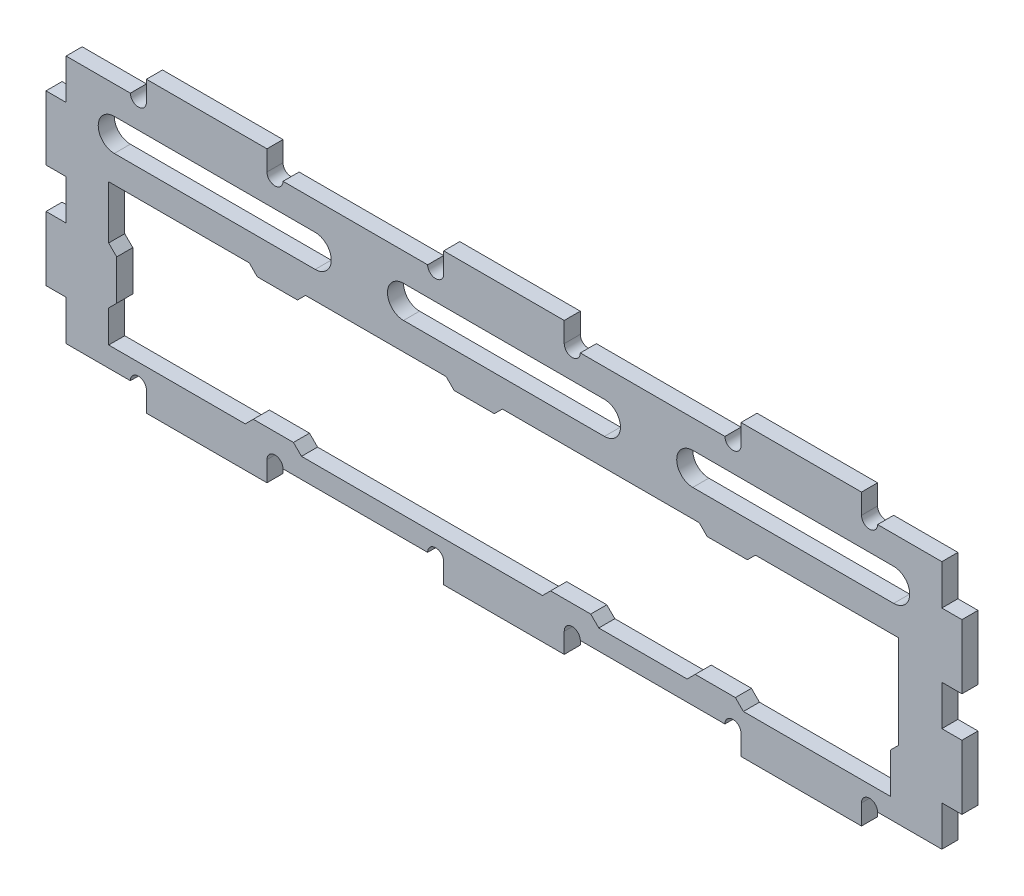
SolidWorks part; units mm, degrees
ref_plane "前视基准面" through (0, 0, 0) normal (0, 0, 1) x (1, 0, 0)
ref_plane "上视基准面" through (0, 0, 0) normal (0, 1, 0) x (1, 0, 0)
ref_plane "右视基准面" through (0, 0, 0) normal (1, 0, 0) x (0, 0, -1)
sketch "草图1" plane through (0, 0, 0) normal (0, 0, 1) x (1, 0, 0)
  line L0 (0, 13) -> (109, 13) construction
  line L1 (0, 0) -> (109, 0)
  line L2 (0, 0) -> (0, 31)
  line L3 (0, 31) -> (109, 31)
  line L4 (109, 0) -> (109, 31)
  line L5 (23.3, 3.5) -> (28.3, 3.5)
  line L6 (23.8, 19.1) -> (28.8, 19.1)
  line L7 (6.3, 12.5) -> (6.3, 7.5)
  line L8 (102.6, 7.5) -> (102.6, 2.5)
  line L9 (65.3, 3.5) -> (60.3, 3.5)
  line L10 (78.3, 3.5) -> (83.3, 3.5)
  line L11 (23.3, 3.5) -> (22.3, 2.5)
  line L12 (22.3, 2.5) -> (5.3, 2.5)
  line L13 (5.3, 2.5) -> (5.3, 6.5)
  line L14 (5.3, 6.5) -> (6.3, 7.5)
  line L15 (28.3, 3.5) -> (29.3, 2.5)
  line L16 (60.3, 3.5) -> (59.3, 2.5)
  line L17 (65.3, 3.5) -> (66.3, 2.5)
  line L18 (78.3, 3.5) -> (77.3, 2.5)
  line L19 (83.3, 3.5) -> (84.3, 2.5)
  line L20 (29.3, 2.5) -> (59.3, 2.5)
  line L21 (66.3, 2.5) -> (77.3, 2.5)
  line L22 (84.3, 2.5) -> (102.6, 2.5)
  line L23 (102.6, 7.5) -> (103.6, 8.5)
  line L24 (103.6, 8.5) -> (103.6, 20.1)
  line L25 (23.8, 19.1) -> (22.8, 20.1)
  line L26 (22.8, 20.1) -> (5.3, 20.1)
  line L27 (6.3, 12.5) -> (5.3, 13.5)
  line L28 (5.3, 13.5) -> (5.3, 20.1)
  line L29 (48.3, 19.1) -> (53.3, 19.1)
  line L30 (79.8, 19.1) -> (84.8, 19.1)
  line L31 (84.8, 19.1) -> (85.8, 20.1)
  line L32 (79.8, 19.1) -> (78.8, 20.1)
  line L33 (53.3, 19.1) -> (54.3, 20.1)
  line L34 (48.3, 19.1) -> (47.3, 20.1)
  line L35 (28.8, 19.1) -> (29.8, 20.1)
  line L36 (29.8, 20.1) -> (47.3, 20.1)
  line L37 (54.3, 20.1) -> (78.8, 20.1)
  line L38 (85.8, 20.1) -> (103.6, 20.1)
  point P15 (6.3, 10)
  dimension "D1" = 31
  dimension "D2" = 109
  dimension "D3" = 13
  dimension "D4" = 9.5
  dimension "D5" = 15.6
  dimension "D6" = 96.3
  dimension "D7" = 6.4
  dimension "D8" = 17
  dimension "D9" = 5
  dimension "D10" = 59
  dimension "D11" = 5
  dimension "D12" = 77
  dimension "D13" = 5
  dimension "D14" = 10
  dimension "D15" = 5
  dimension "D16" = 135
  dimension "D17" = 1
  dimension "D18" = 1
  dimension "D19" = 5
  dimension "D20" = 22.5
  dimension "D21" = 5
  dimension "D22" = 1
  dimension "D23" = 47
  dimension "D24" = 5
  dimension "D25" = 78.5
  dimension "D26" = 5
  dimension "D28" = 1
extrude "凸台-拉伸1" add sketch "草图1" along normal blind 2
sketch "草图2" plane through (0, 0, 2) normal (0, 0, 1) x (1, 0, 0)
  line L0 (0, 31) -> (0, 0) construction
  line L1 (0, 26) -> (-2.5, 26)
  line L2 (0, 26) -> (0, 18)
  line L3 (0, 18) -> (-2.5, 18)
  line L4 (-2.5, 26) -> (-2.5, 18)
  line L5 (109, 31) -> (0, 31) construction
  line L6 (0, 5) -> (-2.5, 5)
  line L7 (0, 5) -> (0, 13)
  line L8 (0, 13) -> (-2.5, 13)
  line L9 (-2.5, 5) -> (-2.5, 13)
  line L10 (0, 0) -> (109, 0) construction
  line L11 (54.5, 31) -> (54.5, 0) construction
  line L12 (111.5, 5) -> (111.5, 13)
  line L13 (109, 13) -> (111.5, 13)
  line L14 (109, 5) -> (109, 13)
  line L15 (109, 5) -> (111.5, 5)
  line L16 (111.5, 26) -> (111.5, 18)
  line L17 (109, 18) -> (111.5, 18)
  line L18 (109, 26) -> (109, 18)
  line L19 (109, 26) -> (111.5, 26)
  dimension "D1" = 5
  dimension "D2" = 5
  dimension "D3" = 8
  dimension "D4" = 8
  dimension "D5" = 2.5
extrude "凸台-拉伸2" add sketch "草图2" against normal up to surface (2 mm away) up to face at (54.5, 15.5, 0)
sketch "草图3" plane through (0, 0, 2) normal (0, 0, 1) x (1, 0, 0)
  line L0 (0, 31) -> (0, 26) construction
  line L1 (109, 31) -> (0, 31) construction
  line L2 (10, 31) -> (25, 31)
  line L3 (10, 31) -> (10, 33.5)
  line L4 (10, 33.5) -> (25, 33.5)
  line L5 (25, 31) -> (25, 33.5)
  line L6 (47, 31) -> (62, 31)
  line L7 (47, 31) -> (47, 33.5)
  line L8 (47, 33.5) -> (62, 33.5)
  line L9 (62, 31) -> (62, 33.5)
  line L10 (99, 31) -> (84, 31)
  line L11 (99, 31) -> (99, 33.5)
  line L12 (99, 33.5) -> (84, 33.5)
  line L13 (84, 31) -> (84, 33.5)
  line L14 (109, 26) -> (109, 31) construction
  line L15 (0, 15.5) -> (109, 15.5) construction
  line L16 (0, 18) -> (0, 13) construction
  line L17 (109, 13) -> (109, 18) construction
  line L18 (84, 0) -> (84, -2.5)
  line L19 (99, -2.5) -> (84, -2.5)
  line L20 (99, 0) -> (99, -2.5)
  line L21 (99, 0) -> (84, 0)
  line L22 (62, 0) -> (62, -2.5)
  line L23 (47, -2.5) -> (62, -2.5)
  line L24 (47, 0) -> (47, -2.5)
  line L25 (47, 0) -> (62, 0)
  line L26 (25, 0) -> (25, -2.5)
  line L27 (10, -2.5) -> (25, -2.5)
  line L28 (10, 0) -> (10, -2.5)
  line L29 (10, 0) -> (25, 0)
  point P18 (54.5, 33.5)
  dimension "D1" = 10
  dimension "D2" = 10
  dimension "D3" = 15
  dimension "D4" = 15
  dimension "D5" = 2.5
  dimension "D6" = 54.5
  dimension "D7" = 15
extrude "凸台-拉伸3" add sketch "草图3" against normal up to surface (2 mm away) up to face at (54.5, 15.5, 0)
sketch "草图4" plane through (0, 0, 2) normal (0, 0, 1) x (1, 0, 0)
  line L0 (8, 31) -> (10, 31)
  line L1 (10, 31) -> (0, 31) construction
  line L2 (17.5, 33.5) -> (17.5, -2.5) construction
  line L3 (25, 33.5) -> (10, 33.5) construction
  line L4 (10, -2.5) -> (25, -2.5) construction
  line L5 (27, 31) -> (25, 31)
  line L6 (36, 31) -> (36, 0) construction
  line L7 (47, 31) -> (25, 31) construction
  line L8 (25, 0) -> (47, 0) construction
  line L9 (45, 31) -> (47, 31)
  line L10 (54.5, 33.5) -> (54.5, -2.5) construction
  line L11 (62, 33.5) -> (47, 33.5) construction
  line L12 (47, -2.5) -> (62, -2.5) construction
  line L13 (64, 31) -> (62, 31)
  line L14 (82, 31) -> (84, 31)
  line L15 (101, 31) -> (99, 31)
  line L16 (0, 15.5) -> (109, 15.5) construction
  line L17 (0, 18) -> (0, 13) construction
  line L18 (109, 13) -> (109, 18) construction
  line L19 (101, 0) -> (99, 0)
  line L20 (82, 0) -> (84, 0)
  line L21 (64, 0) -> (62, 0)
  line L22 (45, 0) -> (47, 0)
  line L23 (27, 0) -> (25, 0)
  line L24 (8, 0) -> (10, 0)
  arc A0 (10, 31) -> (8, 31) centre (9, 31) cw
  arc A1 (25, 31) -> (27, 31) centre (26, 31) ccw
  arc A2 (47, 31) -> (45, 31) centre (46, 31) cw
  arc A3 (62, 31) -> (64, 31) centre (63, 31) ccw
  arc A4 (84, 31) -> (82, 31) centre (83, 31) cw
  arc A5 (99, 31) -> (101, 31) centre (100, 31) ccw
  arc A6 (99, 0) -> (101, 0) centre (100, 0) cw
  arc A7 (84, 0) -> (82, 0) centre (83, 0) ccw
  arc A8 (62, 0) -> (64, 0) centre (63, 0) cw
  arc A9 (47, 0) -> (45, 0) centre (46, 0) ccw
  arc A10 (25, 0) -> (27, 0) centre (26, 0) cw
  arc A11 (10, 0) -> (8, 0) centre (9, 0) ccw
  dimension "D1" = 1
extrude "切除-拉伸1" cut sketch "草图4" against normal through all
sketch "草图5" plane through (0, 0, 2) normal (0, 0, 1) x (1, 0, 0)
  line L0 (6, 25.5) -> (31, 25.5) construction
  line L1 (6, 27.5) -> (31, 27.5)
  line L2 (6, 23.5) -> (31, 23.5)
  line L3 (0, 31) -> (0, 26) construction
  line L4 (42, 25.5) -> (67, 25.5) construction
  line L5 (42, 27.5) -> (67, 27.5)
  line L6 (42, 23.5) -> (67, 23.5)
  line L7 (78, 25.5) -> (103, 25.5) construction
  line L8 (78, 27.5) -> (103, 27.5)
  line L9 (78, 23.5) -> (103, 23.5)
  line L10 (109, 26) -> (109, 31) construction
  line L11 (8, 31) -> (0, 31) construction
  arc A0 (6, 27.5) -> (6, 23.5) centre (6, 25.5) ccw
  arc A1 (31, 23.5) -> (31, 27.5) centre (31, 25.5) ccw
  arc A2 (42, 27.5) -> (42, 23.5) centre (42, 25.5) ccw
  arc A3 (67, 23.5) -> (67, 27.5) centre (67, 25.5) ccw
  arc A4 (78, 27.5) -> (78, 23.5) centre (78, 25.5) ccw
  arc A5 (103, 23.5) -> (103, 27.5) centre (103, 25.5) ccw
  point P2 (18.5, 25.5)
  point P13 (54.5, 25.5)
  point P20 (90.5, 25.5)
  dimension "D5" = 2
  dimension "D1" = 25
  dimension "D2" = 6
  dimension "D4" = 6
  dimension "D6" = 3.5
  dimension "D3" = 3
extrude "切除-拉伸2" cut sketch "草图5" against normal through all
